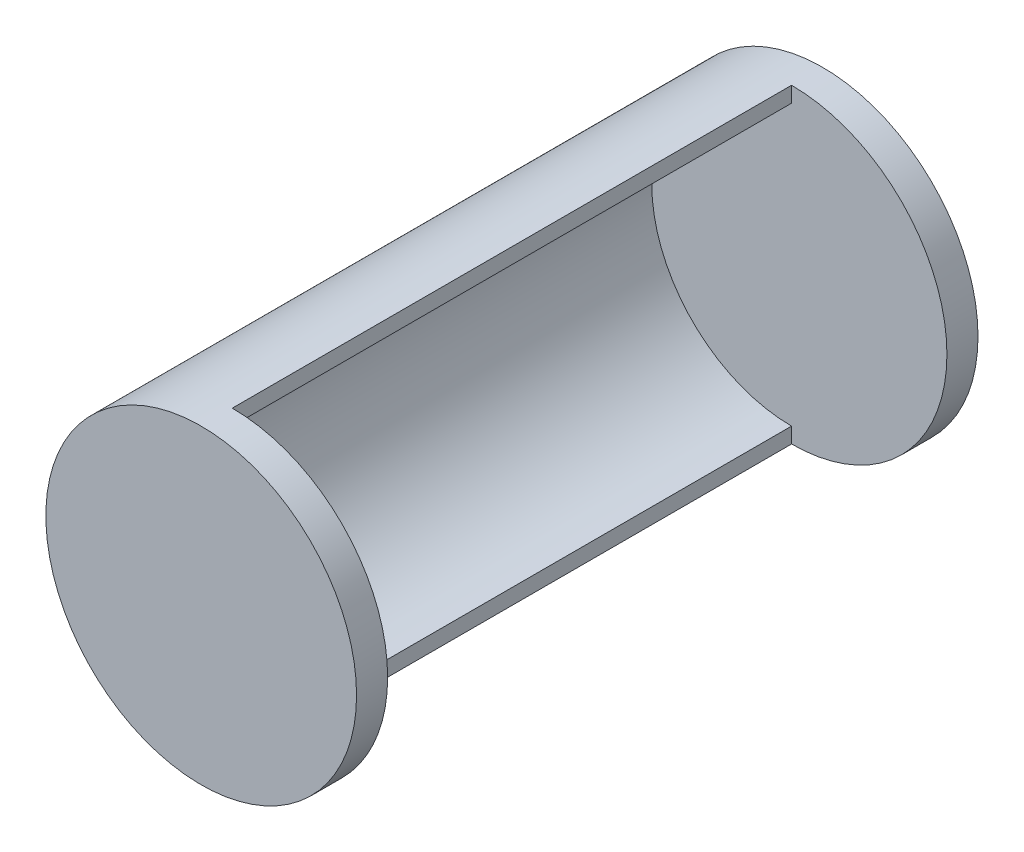
SolidWorks part; units mm, degrees
ref_plane "Front Plane" through (0, 0, 0) normal (1, 0, 0) x (0, 1, 0)
ref_plane "Top Plane" through (0, 0, 0) normal (0, 0, 1) x (0, 1, 0)
ref_plane "Right Plane" through (0, 0, 0) normal (0, 1, 0) x (-1, 0, 0)
sketch "Sketch1" plane through (0, 0, 0) normal (0, 0, 1) x (0, 1, 0)
  circle A0 centre (0, 0) radius 50
  dimension "D1" = 100
extrude "Boss-Extrude1" add sketch "Sketch1" along normal blind 10
sketch "Sketch2" plane through (0, 0, 10) normal (0, 0, 1) x (1, 0, 0)
  line L0 (0, -50) -> (0, 50) construction
  line L1 (0, 50) -> (0, 45)
  line L2 (0, -50) -> (0, -45)
  arc A0 (0, 50) -> (0, -50) centre (0, 0) ccw
  arc A1 (0, 45) -> (0, -45) centre (0, 0) ccw
  dimension "D1" = 50
  dimension "D2" = 5
extrude "Boss-Extrude2" add sketch "Sketch2" along normal blind 180
sketch "Sketch3" plane through (0, 0, 190) normal (0, 0, 1) x (1, 0, 0)
  circle A0 centre (0, 0) radius 50
extrude "Boss-Extrude3" add sketch "Sketch3" along normal blind 10
